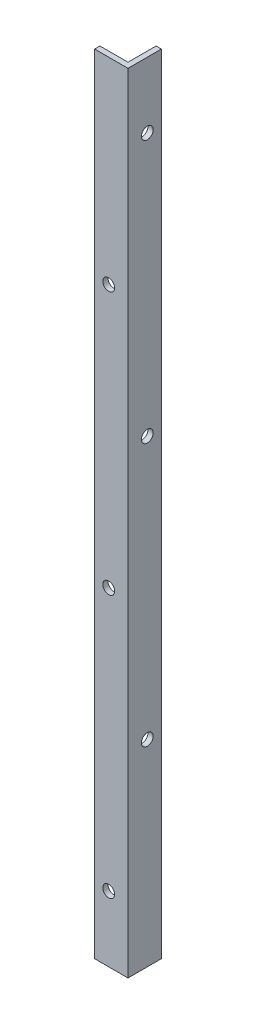
SolidWorks part; units mm, degrees
material "Alumina"
ref_plane "Front Plane" through (0, 0, 0) normal (0, 0, 1) x (1, 0, 0)
ref_plane "Top Plane" through (0, 0, 0) normal (0, 1, 0) x (1, 0, 0)
ref_plane "Right Plane" through (0, 0, 0) normal (1, 0, 0) x (0, 0, -1)
sketch "Sketch1" plane through (0, 0, 0) normal (0, 1, 0) x (1, 0, 0)
  line L0 (0, 0) -> (0, 12.7)
  line L1 (0, 0) -> (-12.7, 0)
  line L2 (-2, 2) -> (-2, 12.7)
  line L3 (-2, 2) -> (-12.7, 2)
  line L4 (-2, 12.7) -> (0, 12.7)
  line L5 (-12.7, 2) -> (-12.7, -0.2944)
  dimension "D1" = 12.7
  dimension "D2" = 12.7
  dimension "D3" = 2
extrude "Boss-Extrude1" add sketch "Sketch1" along normal blind 300 contours L3 L5 L1 L0 L4 L2
sketch "Sketch2" plane through (-2, 0, 0) normal (-1, 0, 0) x (0, 0, 1)
  line L0 (-7.35, 300) -> (-7.35, 0) construction
  line L1 (-2, 300) -> (-12.7, 300) construction
  line L2 (-2, 0) -> (-12.7, 0) construction
  circle A0 centre (-7.35, 275) radius 2.25
  circle A1 centre (-7.35, 175) radius 2.25
  circle A2 centre (-7.35, 75) radius 2.25
  dimension "D1" = 4.5
  dimension "D2" = 25
extrude "Cut-Extrude1" cut sketch "Sketch2" against normal blind 10
sketch "Sketch3" plane through (0, 0, -2) normal (0, 0, -1) x (-1, 0, 0)
  line L0 (7.35, 300) -> (7.35, 0) construction
  line L1 (2, 300) -> (12.7, 300) construction
  line L2 (2, 0) -> (12.7, 0) construction
  circle A0 centre (7.35, 225) radius 2.25
  circle A1 centre (7.35, 125) radius 2.25
  circle A2 centre (7.35, 25) radius 2.25
  dimension "D1" = 4.5
  dimension "D2" = 75
extrude "Cut-Extrude2" cut sketch "Sketch3" against normal blind 10
